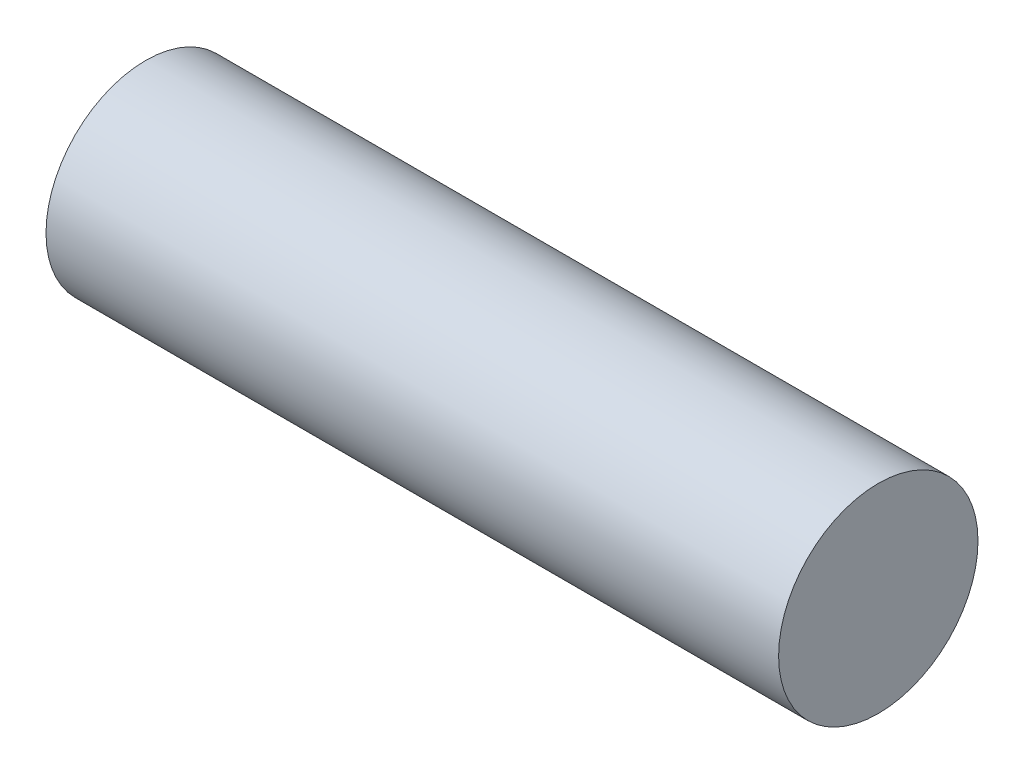
SolidWorks part; units mm, degrees
ref_plane "Plano frontal" through (0, 0, 0) normal (0, 0, 1) x (1, 0, 0)
ref_plane "Plano superior" through (0, 0, 0) normal (0, 1, 0) x (1, 0, 0)
ref_plane "Plano direito" through (0, 0, 0) normal (1, 0, 0) x (0, 0, -1)
sketch "Esboço1" plane through (0, 0, 0) normal (1, 0, 0) x (0, 0, -1)
  circle A0 centre (0, 0) radius 9.05
  dimension "D1" = 18.1
extrude "Ressalto-extrusão1" add sketch "Esboço1" along normal blind 66.5
